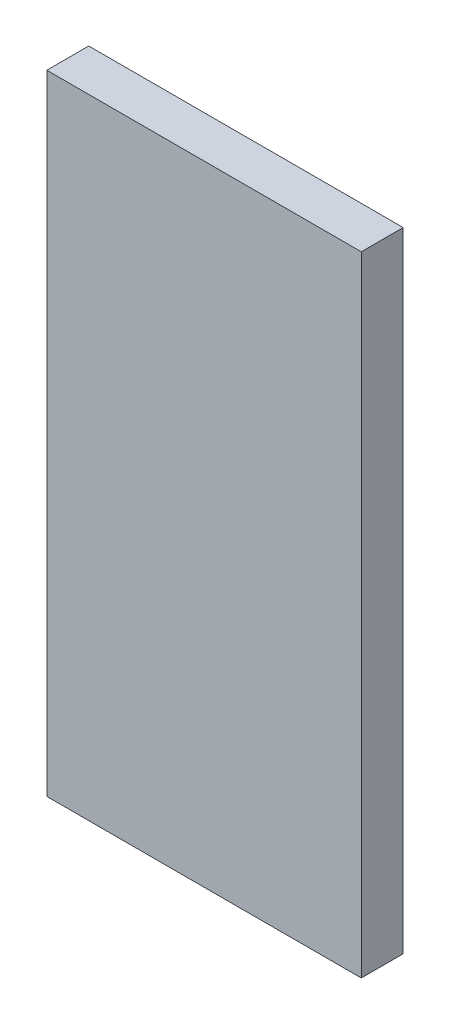
SolidWorks part; units mm, degrees
ref_plane "Front Plane" through (0, 0, 0) normal (0, 0, 1) x (1, 0, 0)
ref_plane "Top Plane" through (0, 0, 0) normal (0, 1, 0) x (1, 0, 0)
ref_plane "Right Plane" through (0, 0, 0) normal (1, 0, 0) x (0, 0, -1)
sketch "Sketch1" plane through (0, 0, 0) normal (0, 0, 1) x (1, 0, 0)
  line L1 (7.5, -15) -> (-7.5, -15)
  line L2 (7.5, -15) -> (7.5, 15)
  line L3 (7.5, 15) -> (-7.5, 15)
  line L4 (-7.5, -15) -> (-7.5, 15)
  line L5 (7.5, -15) -> (-7.5, 15) construction
  line L6 (7.5, 15) -> (-7.5, -15) construction
  point P0 (0, 0)
  dimension "D1" = 15
  dimension "D2" = 30
extrude "Boss-Extrude1" add sketch "Sketch1" along normal blind 2
